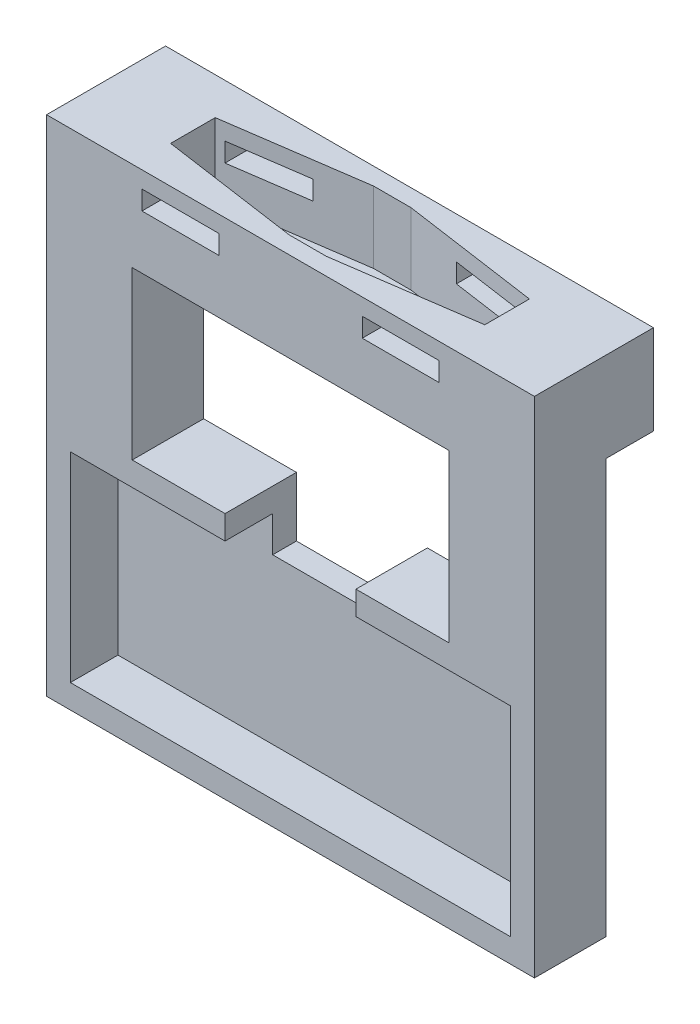
SolidWorks part; units mm, degrees
ref_plane "Front Plane" through (0, 0, 0) normal (0, 0, 1) x (1, 0, 0)
ref_plane "Top Plane" through (0, 0, 0) normal (0, 1, 0) x (1, 0, 0)
ref_plane "Right Plane" through (0, 0, 0) normal (1, 0, 0) x (0, 0, -1)
sketch "Sketch1" plane through (0, 0, 0) normal (0, 0, 1) x (1, 0, 0)
  line L1 (0, 0) -> (52.07, 0)
  line L2 (0, 0) -> (0, 26.416)
  line L3 (0, 26.416) -> (52.07, 26.416)
  line L4 (52.07, 0) -> (52.07, 26.416)
  dimension "D1" = 52.07
  dimension "D2" = 26.416
extrude "Ultrasonic Holder Extrude" add sketch "Sketch1" along normal blind 7.62
shell "Ultrasonic Cutout" thickness 2.54
sketch "Sketch2" plane through (0, 0, 0) normal (0, -1, 0) x (1, 0, 0)
  line L0 (0, 7.62) -> (52.07, 7.62) construction
  line L1 (19.05, 7.62) -> (33.02, 7.62)
  line L2 (19.05, 7.62) -> (19.05, 0)
  line L3 (19.05, 0) -> (33.02, 0)
  line L4 (33.02, 7.62) -> (33.02, 0)
  line L5 (0, 0) -> (52.07, 0) construction
  line L6 (0, 7.62) -> (0, 0) construction
  dimension "D1" = 13.97
  dimension "D2" = 19.05
extrude "Ultrasonic Wire Hole" cut sketch "Sketch2" along normal blind 6.35 and the other way blind 12.7 from surface at -26.416 starting at face at (26.035, 26.416, 3.81)
sketch "Sketch7" plane through (0, 0, 0) normal (-1, 0, 0) x (0, 0, 1)
  line L0 (7.62, 26.416) -> (7.62, 0) construction
  line L3 (7.62, 44.196) -> (-5.08, 44.196)
  line L4 (-5.08, 53.7564) -> (-5.08, 44.196)
  line L5 (7.62, 26.416) -> (0, 26.416) construction
  line L6 (7.62, 44.196) -> (7.62, 53.7564)
  line L8 (7.62, 53.7564) -> (-5.08, 53.7564)
  dimension "D1" = 12.7
  dimension "D2" = 0
  dimension "D3" = 9.5604
  dimension "D4" = 17.78
extrude "Servo Holder" add sketch "Sketch7" against normal through all
sketch "Sketch8" plane through (0, 0, 7.62) normal (0, 0, 1) x (1, 0, 0)
  line L1 (9.271, 52.4685) -> (42.799, 52.4685)
  line L2 (9.271, 52.4685) -> (9.271, 48.9125)
  line L3 (9.271, 48.9125) -> (42.799, 48.9125)
  line L4 (42.799, 52.4685) -> (42.799, 48.9125)
  line L9 (0, 44.196) -> (0, 53.7564) construction
  line L10 (52.07, 44.196) -> (52.07, 53.7564) construction
  line L11 (52.07, 53.7564) -> (0, 53.7564) construction
  dimension "D1" = 1.2879
  dimension "D2" = 33.528
  dimension "D3" = 3.556
  dimension "D4" = 9.271
  dimension "D5" = 9.271
sketch "Sketch9" plane through (0, 0, 7.62) normal (0, 0, 1) x (1, 0, 0)
  line L0 (52.07, 44.196) -> (0, 44.196) construction
  line L1 (19.05, 45.4839) -> (33.02, 45.4839)
  line L2 (19.05, 45.4839) -> (19.05, 44.196)
  line L3 (19.05, 44.196) -> (33.02, 44.196)
  line L4 (33.02, 45.4839) -> (33.02, 44.196)
  point P4 (26.035, 44.196)
  point P7 (26.035, 44.196)
  dimension "D1" = 13.97
  dimension "D2" = 0
  dimension "D3" = 0
  dimension "D4" = 1.2879
sketch "Sketch10" plane through (0, 44.196, 0) normal (0, -1, 0) x (1, 0, 0)
  line L0 (0, 0) -> (52.07, 0) construction
  line L1 (0, 7.62) -> (9.144, 7.62)
  line L2 (0, 7.62) -> (0, 0)
  line L3 (0, 0) -> (9.144, 0)
  line L4 (9.144, 7.62) -> (9.144, 0)
  line L5 (42.926, 7.62) -> (52.07, 7.62)
  line L6 (0, -5.08) -> (0, 7.62) construction
  line L7 (42.926, 7.62) -> (42.926, 0)
  line L8 (42.926, 0) -> (52.07, 0)
  line L9 (52.07, 7.62) -> (52.07, 0)
  line L10 (52.07, 7.62) -> (52.07, 0) construction
  line L11 (0, 7.62) -> (52.07, 7.62) construction
  dimension "D1" = 9.144
  dimension "D2" = 0
  dimension "D3" = 7.62
  dimension "D4" = 0
  dimension "D5" = 7.62
  dimension "D6" = 0
  dimension "D7" = 9.144
  dimension "D8" = 0
extrude "Connector" add sketch "Sketch10" along normal blind 20.32 contours L2 L3 L4 L1 | L5 L9 L8 L7
sketch "Sketch11" plane through (0, 53.7564, 0) normal (0, 1, 0) x (1, 0, 0)
sketch "Sketch14" plane through (0, 53.7564, 0) normal (0, 1, 0) x (0, 0, 1)
  line L0 (-1.1112, 42.799) -> (3.6513, 42.799)
  line L2 (-3.2385, 28.0162) -> (-3.2385, 24.0538)
  line L5 (7.62, 52.07) -> (-5.08, 52.07) construction
  line L6 (3.6513, 42.799) -> (5.7785, 28.0162)
  line L7 (-1.1112, 9.271) -> (3.6512, 9.271)
  line L8 (5.7785, 24.0538) -> (5.7785, 28.0162)
  line L9 (-1.1112, 42.799) -> (-3.2385, 28.0162)
  line L10 (-3.2385, 24.0538) -> (-1.1112, 9.271)
  line L11 (3.6512, 9.271) -> (5.7785, 24.0538)
  line L12 (-5.08, 52.07) -> (-5.08, 0) construction
  point P4 (-3.2385, 26.035)
  point P7 (1.27, 52.07)
  dimension "D2" = 9.017
  dimension "D3" = 26.035
  dimension "D4" = 171.811
  dimension "D5" = 3.9624
  dimension "D6" = 3.9624
  dimension "D7" = 4.7625
  dimension "D8" = 1.8415
  dimension "D9" = 171.811
  dimension "D10" = 171.811
  dimension "D11" = 171.811
extrude "Servo Cutout" cut sketch "Sketch14" against normal blind 7.62
sketch "Sketch15" plane through (0, 0, 7.62) normal (0, 0, 1) x (1, 0, 0)
  line L5 (18.3968, 51.9784) -> (10.181, 51.9784)
  line L6 (10.181, 51.9784) -> (10.181, 49.9464)
  line L7 (10.181, 49.9464) -> (18.3968, 49.9464)
  line L8 (18.3968, 49.9464) -> (18.3968, 51.9784)
  line L11 (52.07, 53.7564) -> (0, 53.7564) construction
  line L12 (0, 53.7564) -> (0, 0) construction
  line L13 (41.91, 51.9784) -> (33.6942, 51.9784)
  line L14 (33.6942, 51.9784) -> (33.6942, 49.9464)
  line L15 (33.6942, 49.9464) -> (41.91, 49.9464)
  line L16 (41.91, 49.9464) -> (41.91, 51.9784)
  line L17 (52.07, 0) -> (52.07, 53.7564) construction
  dimension "D1" = 10.16
  dimension "D2" = 1.778
  dimension "D3" = 10.181
  dimension "D4" = 1.778
  dimension "D5" = 2.032
  dimension "D6" = 2.032
extrude "Servo Securer Cut" cut sketch "Sketch15" against normal through all both and the other way through all
